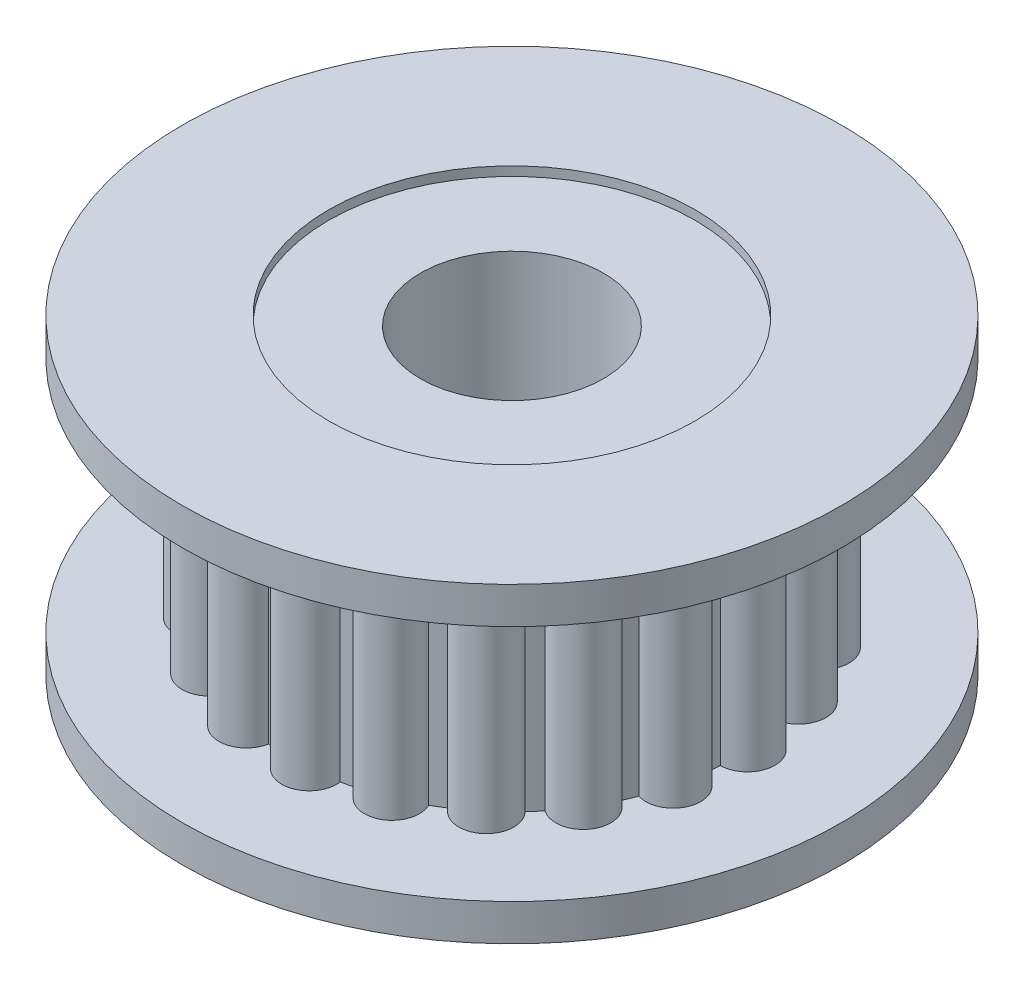
SolidWorks part; units mm, degrees
material "6061-T6 (SS)"
ref_plane "前视基准面" through (0, 0, 0) normal (0, 0, 1) x (1, 0, 0)
ref_plane "上视基准面" through (0, 0, 0) normal (0, 1, 0) x (1, 0, 0)
ref_plane "右视基准面" through (0, 0, 0) normal (1, 0, 0) x (0, 0, -1)
sketch "草图1" plane through (0, 0, 0) normal (0, 0, 1) x (1, 0, 0)
  line L0 (0, 36.5233) -> (0, -21.7737) construction
  line L1 (0, 0) -> (-51.616, 0) construction
  line L2 (-9, 4.25) -> (-5, 4.25)
  line L3 (-5, 4.25) -> (-5, 4)
  line L4 (-5, 4) -> (-2.5, 4)
  line L5 (-2.5, 4) -> (-2.5, -4)
  line L6 (-9, 4.25) -> (-9, 3.25)
  line L7 (-9, 3.25) -> (-6, 3.25)
  line L8 (-6, 3.25) -> (-6, -3.25)
  line L9 (-9, -3.25) -> (-6, -3.25)
  line L10 (-9, -4.25) -> (-9, -3.25)
  line L11 (-5, -4) -> (-2.5, -4)
  line L12 (-5, -4.25) -> (-5, -4)
  line L13 (-9, -4.25) -> (-5, -4.25)
  point P14 (-6, 0)
  point P17 (-2.5, 0)
  dimension "D1" = 6
  dimension "D2" = 3.25
  dimension "D3" = 9
  dimension "D4" = 2.5
  dimension "D5" = 4.25
  dimension "D6" = 1
  dimension "D7" = 4
revolve "旋转1" add sketch "草图1" angle 360 about L0
sketch "草图2" plane through (0, -3.25, 0) normal (0, 1, 0) x (1, 0, 0)
  circle A0 centre (3.879, -4.5775) radius 0.75
  circle A1 centre (0, 0) radius 6 construction
  dimension "D1" = 1.5
extrude "凸台-拉伸1" add sketch "草图2" along normal blind 7
pattern_circular "阵列(圆周)1" count 20 over 360 about axis through (0, 0, 0) along (0, 1, 0) of "凸台-拉伸1"
